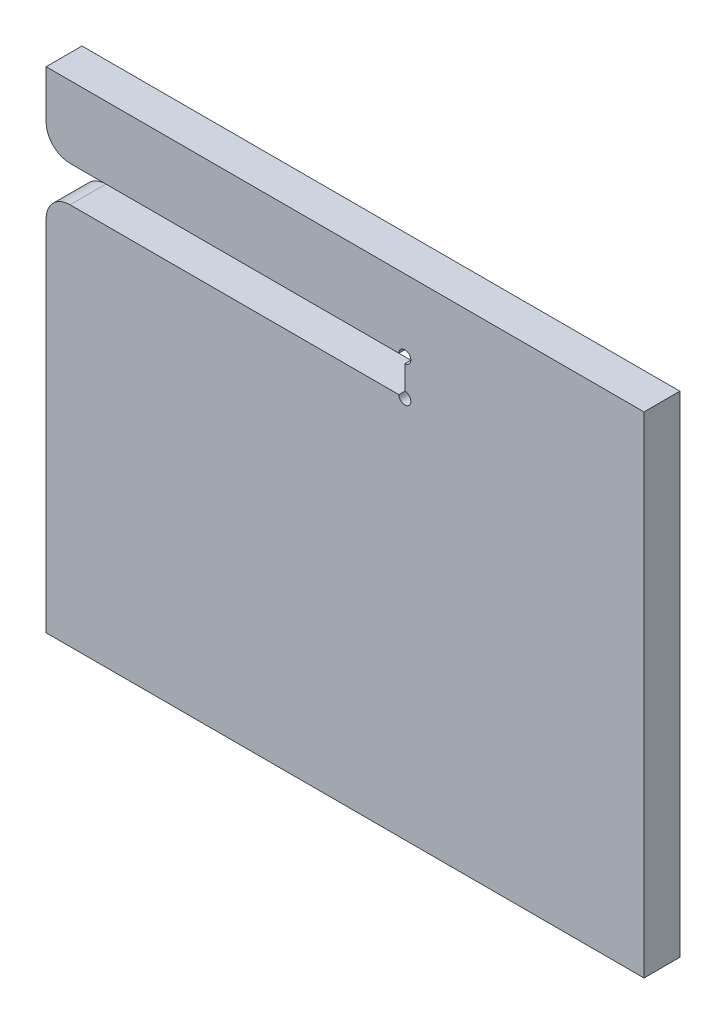
SolidWorks part; units mm, degrees
material "Acrylic (Medium-high impact)"
ref_plane "Front Plane" through (0, 0, 0) normal (0, 0, 1) x (1, 0, 0)
ref_plane "Top Plane" through (0, 0, 0) normal (0, 1, 0) x (1, 0, 0)
ref_plane "Right Plane" through (0, 0, 0) normal (1, 0, 0) x (0, 0, -1)
sketch "Sketch1" plane through (0, 0, 0) normal (0, 0, 1) x (1, 0, 0)
  line L1 (-30, 6) -> (20, 6)
  line L2 (-30, 6) -> (-30, -35)
  line L3 (-30, -35) -> (20, -35)
  line L4 (20, 6) -> (20, -35)
  point P0 (0, 0)
  dimension "D1" = 6
  dimension "D2" = 50
  dimension "D3" = 35
  dimension "D4" = 20
extrude "Boss-Extrude1" add sketch "Sketch1" along normal blind 3
sketch "Sketch2" plane through (0, 0, 0) normal (0, 0, 1) x (1, 0, 0)
  line L0 (-30, 6) -> (-30, -35) construction
  line L1 (-30, 0) -> (-0.5, 0)
  line L2 (-30, 0) -> (-30, -3)
  line L3 (-30, -3) -> (-0.5, -3)
  line L4 (0, -0.5) -> (0, -2.5)
  line L6 (0, 0) -> (0, 6) construction
  line L7 (20, 6) -> (-30, 6) construction
  arc A0 (-0.5, 0) -> (0, -0.5) centre (0, 0) cw
  arc A1 (0, -2.5) -> (-0.5, -3) centre (0, -3) cw
  dimension "D1" = 0.5
  dimension "D2" = 0.5
  dimension "D3" = 3
extrude "Cut-Extrude1" cut sketch "Sketch2" along normal through all
fillet "Fillet1" radius 2 2 edges at (-30, -3, 1.5) (-30, 0, 1.5)
